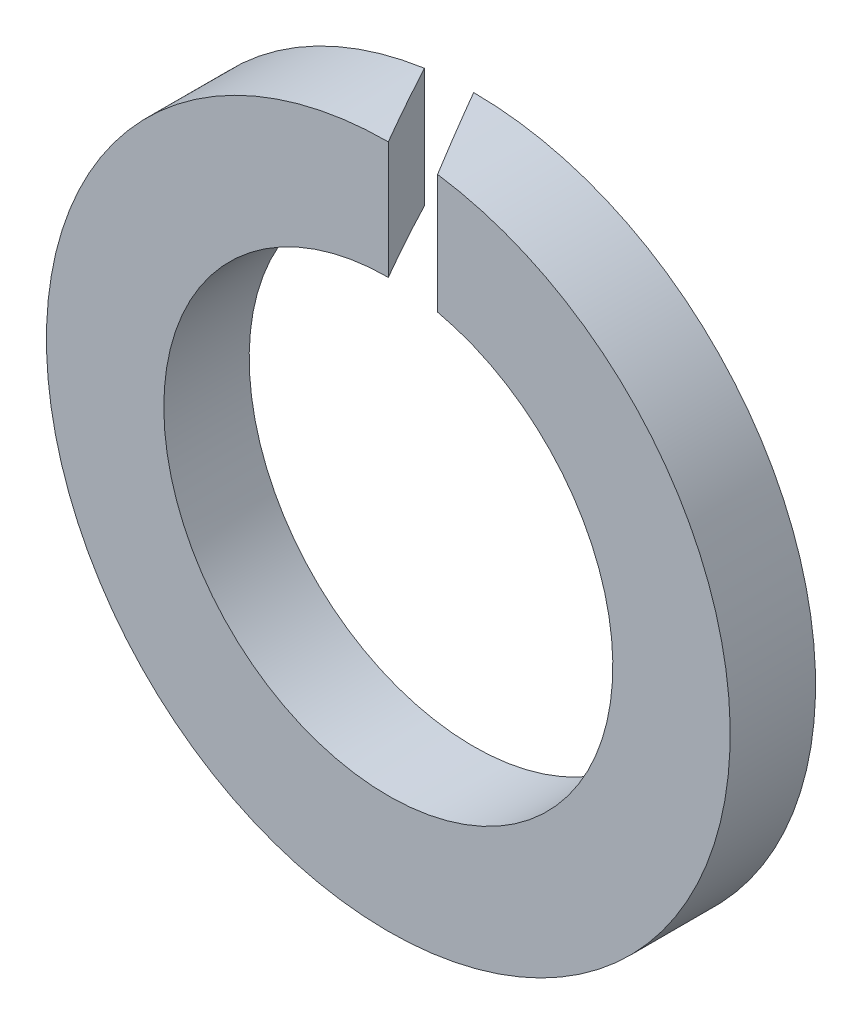
SolidWorks part; units mm, degrees
material "普通碳钢"
ref_plane "前视基准面" through (0, 0, 0) normal (0, 0, 1) x (1, 0, 0)
ref_plane "上视基准面" through (0, 0, 0) normal (0, 1, 0) x (1, 0, 0)
ref_plane "右视基准面" through (0, 0, 0) normal (1, 0, 0) x (0, 0, -1)
sketch "草图1" plane through (0, 0, 0) normal (0, 1, 0) x (1, 0, 0)
  line L0 (16.02, 4) -> (0, 4)
  line L1 (0, 4) -> (0, 0)
  line L2 (0, 0) -> (16.02, 0)
  line L3 (16.02, 0) -> (16.02, 4)
  line L4 (0, 4) -> (0, 0) construction
revolve "旋转1" add sketch "草图1" angle 360 about L4
sketch "草图2" plane through (0, 0, 0) normal (0, 0, 1) x (1, 0, 0)
  line L0 (0, 16.02) -> (0, 10.52)
  line L1 (2.3094, 10.2634) -> (2.3094, 15.8527)
  arc A0 (0, 10.52) -> (2.3094, 10.2634) centre (0, 0) cw
  arc A1 (2.3094, 15.8527) -> (0, 16.02) centre (0, 0) ccw
extrude "切除-拉伸1" cut sketch "草图2" against normal through all
draft "拔模1" type of draft neutral plane draft angle 30 faces to draft 1 face at (0, 13.27, -2) neutral plane through (0, 0, 0) neutral plane normal (0, 0, 1) reverse direction yes parameters "D1"=30
draft "拔模2" type of draft neutral plane draft angle 30 faces to draft 1 face at (2.3094, 13.058, -2) neutral plane through (0, 0, 0) neutral plane normal (0, 0, 1) parameters "D1"=30
ref_plane "基准面1" through (0, 0, 0) normal (0, -1, 0) x (1, 0, 0)
sketch "草图3" plane through (0, 0, 0) normal (0, -1, 0) x (1, 0, 0)
  line L0 (10.52, 0) -> (0, 0)
  line L1 (0, 0) -> (0, -4)
  line L2 (0, -4) -> (10.52, -4)
  line L3 (10.52, -4) -> (10.52, 0)
  line L4 (0, 0) -> (0, -4) construction
revolve "切除-旋转1" cut sketch "草图3" angle 360 about L4
